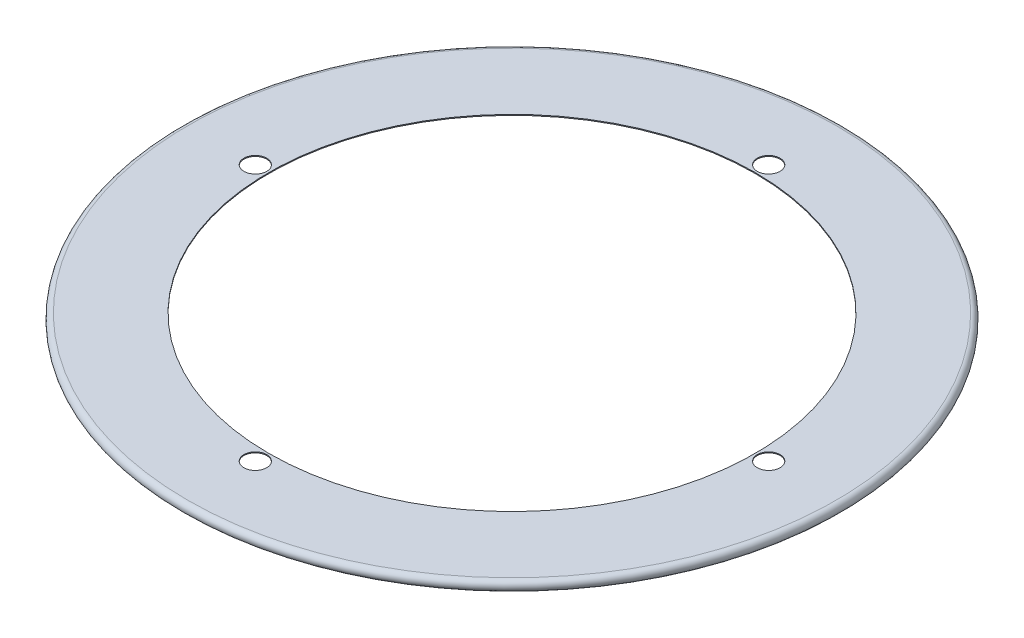
SolidWorks part; units mm, degrees
ref_plane "Front Plane" through (0, 0, 0) normal (0, 0, 1) x (1, 0, 0)
ref_plane "Top Plane" through (0, 0, 0) normal (0, 1, 0) x (1, 0, 0)
ref_plane "Right Plane" through (0, 0, 0) normal (1, 0, 0) x (0, 0, -1)
sketch "Sketch2" plane through (0, 0, 0) normal (0, 0, 1) x (1, 0, 0)
  line L0 (0, 2.4638) -> (38.1, 2.4638)
  line L1 (38.1, 2.4638) -> (38.1, 2.032)
  line L2 (38.1, 2.032) -> (0, 2.032)
  line L3 (0, -2.032) -> (14.9024, -2.032)
  line L4 (14.9024, -2.032) -> (14.9024, -2.4638)
  line L5 (14.9024, -2.4638) -> (0, -2.4638)
  line L6 (152.4, 15.5158) -> (152.4, -14.6803) construction
  line L7 (0, -4.8014) -> (0, 4.3086) construction
  arc A0 (0, 2.4638) -> (0, -2.4638) centre (0, 0) ccw
  arc A1 (0, 2.032) -> (0, -2.032) centre (0, 0) ccw
  dimension "D1" = 2.4638
  dimension "D3" = 2.032
  dimension "D2" = 38.1
  dimension "D4" = 152.4
revolve "Revolve1" add sketch "Sketch2" angle 360 about L6
sketch "Sketch3" plane through (0, 2.4638, 0) normal (0, 1, 0) x (1, 0, 0)
  line L0 (-34.0172, 0) -> (361.469, 0) construction
  circle A0 centre (31.7833, 0) radius 5.36
  circle A1 centre (152.4, 0) radius 120.6167 construction
  circle A2 centre (152.4, 120.6167) radius 5.36
  circle A3 centre (273.0167, 0) radius 5.36
  circle A4 centre (152.4, -120.6167) radius 5.36
  point P13 (152.4, 0)
  dimension "D1" = 4
extrude "Cut-Extrude1" cut sketch "Sketch3" against normal up to surface (0.4318 mm away) up to face at (152.4, 2.032, 114.3)
